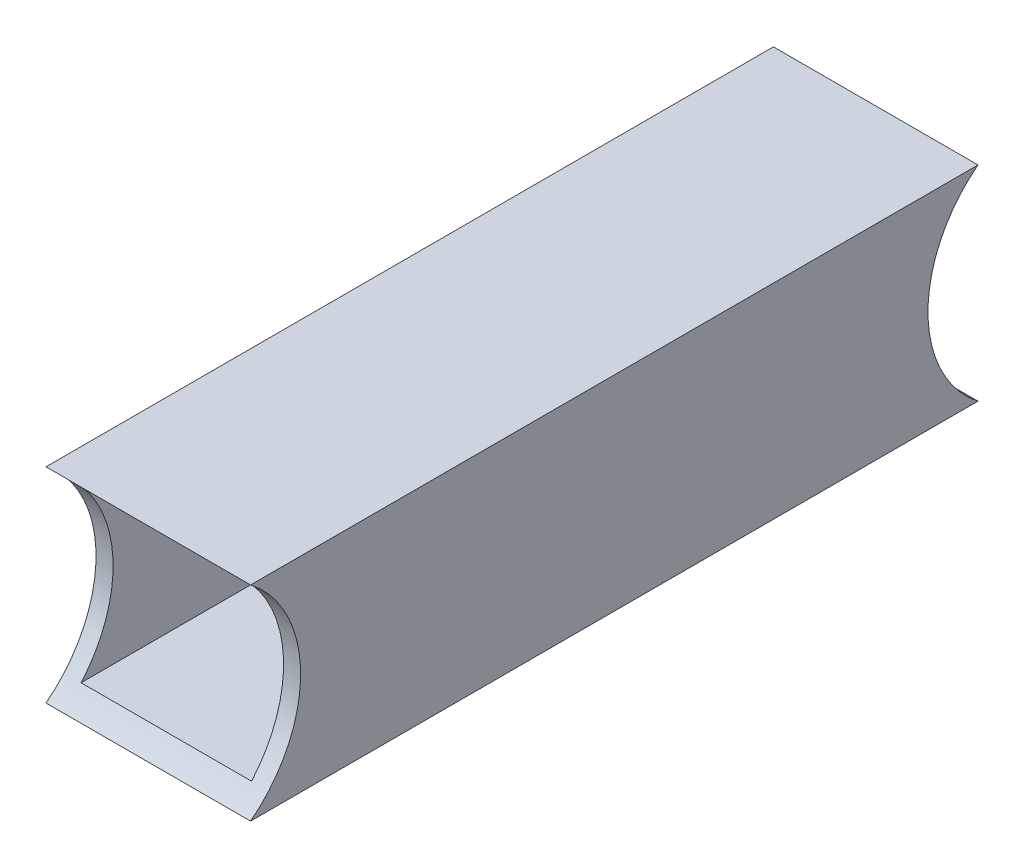
SolidWorks part; units mm, degrees
material "6063-T5"
ref_plane "Front Plane" through (0, 0, 0) normal (0, 0, 1) x (1, 0, 0)
ref_plane "Top Plane" through (0, 0, 0) normal (0, 1, 0) x (1, 0, 0)
ref_plane "Right Plane" through (0, 0, 0) normal (1, 0, 0) x (0, 0, -1)
sketch "Sketch1" plane through (0, 0, 0) normal (1, 0, 0) x (0, 0, -1)
  line L1 (0, 0) -> (165.1, 0)
  line L2 (0, 0) -> (0, 38.1)
  line L3 (0, 38.1) -> (165.1, 38.1)
  line L4 (165.1, 0) -> (165.1, 38.1)
  circle A0 centre (0, 19.05) radius 24.13
  circle A1 centre (165.1, 19.05) radius 24.13
  dimension "D3" = 48.26
  dimension "D1" = 38.1
  dimension "D2" = 165.1
extrude "Boss-Extrude1" add sketch "Sketch1" along normal blind 38.1 contours A1 L3 A0 L1
sketch "Sketch2" plane through (0, 0, 0) normal (0, 0, 1) x (1, 0, 0)
  line L0 (3.175, 34.925) -> (3.175, 3.175)
  line L1 (3.175, 3.175) -> (34.925, 3.175)
  line L2 (34.925, 3.175) -> (34.925, 34.925)
  line L3 (34.925, 34.925) -> (3.175, 34.925)
  line L4 (0, 38.1) -> (0, 0)
  line L5 (0, 0) -> (38.1, 0)
  line L6 (38.1, 0) -> (38.1, 38.1)
  line L7 (38.1, 38.1) -> (0, 38.1)
  line L8 (0, 38.1) -> (0, 0) construction
  line L9 (0, 0) -> (38.1, 0) construction
  line L10 (38.1, 0) -> (38.1, 38.1) construction
  line L11 (38.1, 38.1) -> (0, 38.1) construction
  dimension "D1" = 0
  dimension "D2" = 3.175
extrude "Cut-Extrude1" cut sketch "Sketch2" against normal through all
